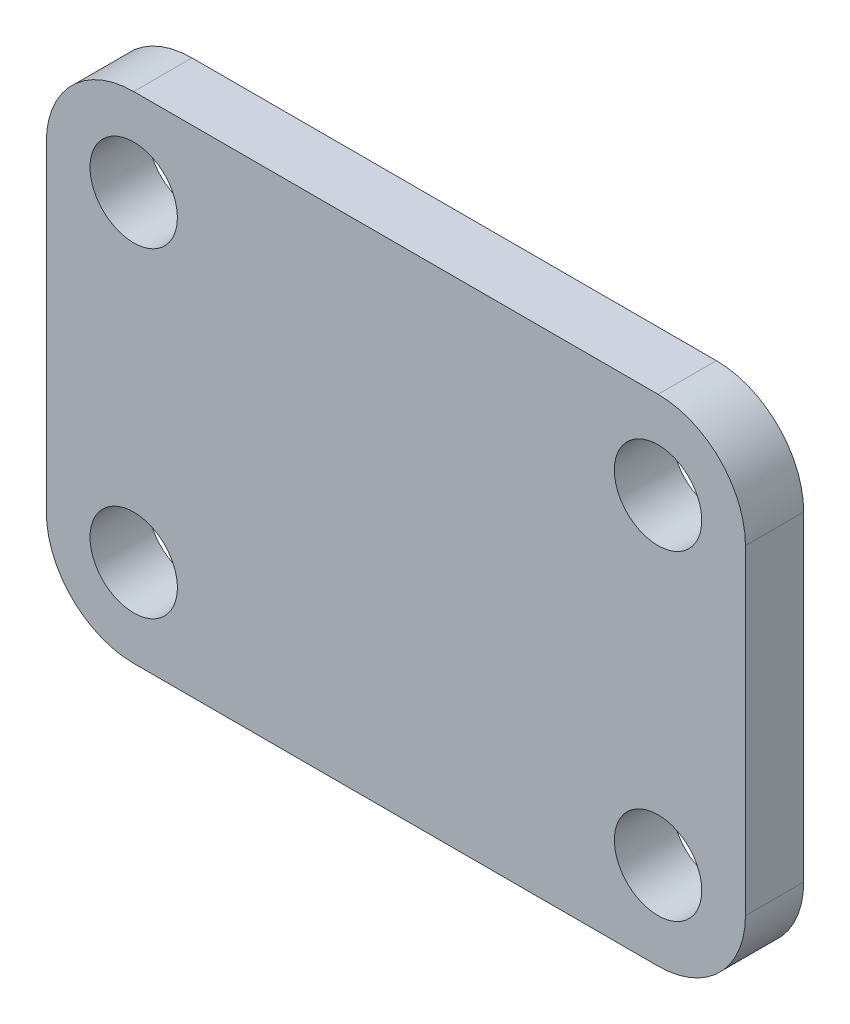
SolidWorks part; units mm, degrees
material "Liga 1060"
ref_plane "Plano frontal" through (0, 0, 0) normal (0, 0, 1) x (1, 0, 0)
ref_plane "Plano superior" through (0, 0, 0) normal (0, 1, 0) x (1, 0, 0)
ref_plane "Plano direito" through (0, 0, 0) normal (1, 0, 0) x (0, 0, -1)
sketch "Esboço1" plane through (0, 0, 0) normal (0, 0, 1) x (1, 0, 0)
  line L0 (0, 0) -> (0, 8.5) construction
  line L1 (-12, 8.5) -> (12, 8.5)
  line L2 (-12, 8.5) -> (-12, -8.5)
  line L3 (-12, -8.5) -> (12, -8.5)
  line L4 (12, 8.5) -> (12, -8.5)
  line L5 (-12, 8.5) -> (12, -8.5) construction
  line L6 (-12, -8.5) -> (12, 8.5) construction
  line L7 (0, 0) -> (-12, 0) construction
  circle A0 centre (-9, 5.5) radius 1.5
  circle A1 centre (9, 5.5) radius 1.5
  circle A2 centre (9, -5.5) radius 1.5
  circle A3 centre (-9, -5.5) radius 1.5
  point P0 (0, 0)
  dimension "D1" = 3
  dimension "D2" = 11
  dimension "D3" = 18
  dimension "D4" = 24
  dimension "D5" = 3
extrude "Ressalto-extrusão1" add sketch "Esboço1" along normal mid plane 2
fillet "Filete1" radius 3 4 edges at (12, -8.5, 0) (-12, -8.5, 0) (-12, 8.5, 0) (12, 8.5, 0)
